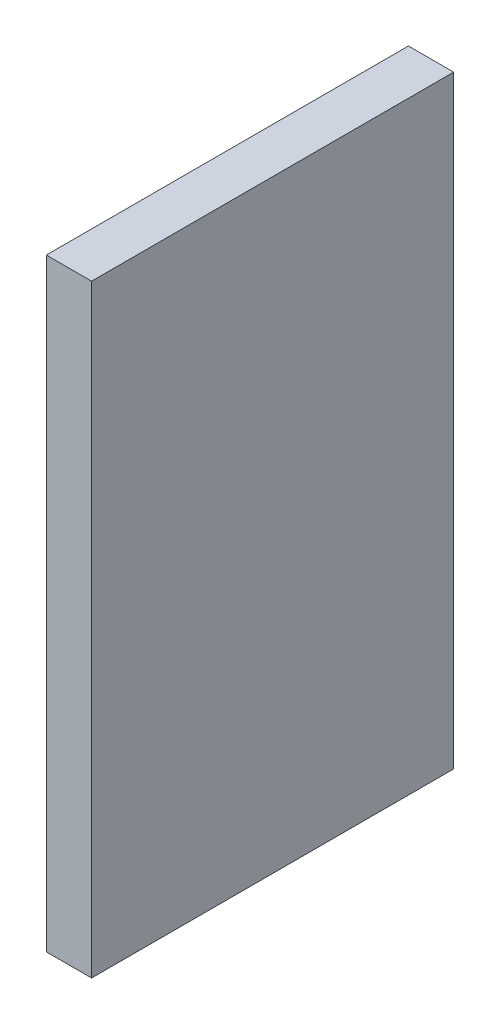
SolidWorks part; units mm, degrees
ref_plane "Front Plane" through (0, 0, 0) normal (1, 0, 0) x (0, 1, 0)
ref_plane "Top Plane" through (0, 0, 0) normal (0, 0, 1) x (0, 1, 0)
ref_plane "Right Plane" through (0, 0, 0) normal (0, 1, 0) x (-1, 0, 0)
sketch "Sketch1" plane through (0, 0, 0) normal (1, 0, 0) x (0, 1, 0)
  line L1 (-100, -60) -> (100, -60)
  line L2 (-100, -60) -> (-100, 60)
  line L3 (-100, 60) -> (100, 60)
  line L4 (100, -60) -> (100, 60)
  line L5 (-100, -60) -> (100, 60) construction
  line L6 (-100, 60) -> (100, -60) construction
extrude "Boss-Extrude1" add sketch "Sketch1" along normal blind 15
